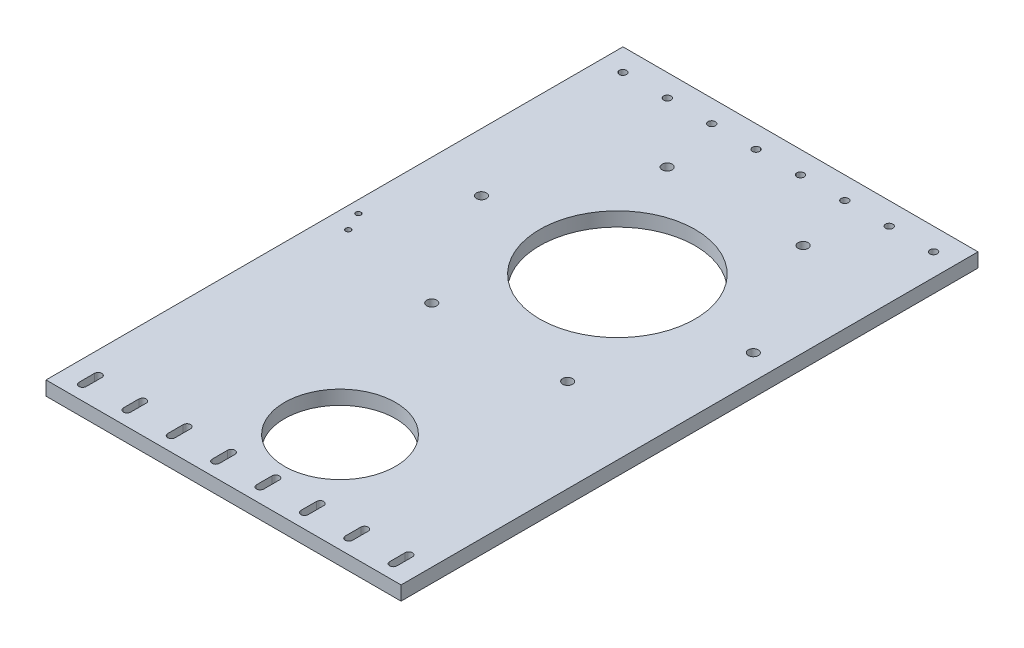
SolidWorks part; units mm, degrees
ref_plane "Front Plane" through (0, 0, 0) normal (0, 0, 1) x (1, 0, 0)
ref_plane "Top Plane" through (0, 0, 0) normal (0, 1, 0) x (1, 0, 0)
ref_plane "Right Plane" through (0, 0, 0) normal (1, 0, 0) x (0, 0, -1)
sketch "Sketch1" plane through (0, 0, 0) normal (0, 1, 0) x (1, 0, 0)
  line L0 (87.5, 260) -> (87.5, 0) construction
  line L1 (0, 0) -> (160, 0)
  line L2 (0, 0) -> (0, 260)
  line L3 (0, 260) -> (160, 260)
  line L4 (160, 0) -> (160, 260)
  line L5 (87.5, 170) -> (148.75, 170) construction
  line L6 (10, 6.5) -> (10, 13.5) construction
  line L7 (5.4755, 135.2989) -> (9.5163, 126.7011) construction
  line L8 (22, 0) -> (22, 260) construction
  line L9 (22, 136) -> (0, 136) construction
  line L10 (22, 126) -> (0, 126) construction
  line L11 (0, 136) -> (0, 126) construction
  line L12 (17.3003, 136) -> (22, 126) construction
  line L13 (8.35, 6.5) -> (8.35, 13.5)
  line L14 (11.65, 6.5) -> (11.65, 13.5)
  line L15 (10, 250) -> (10, 0) construction
  line L16 (31.65, 6.5) -> (31.65, 13.5)
  line L17 (28.35, 6.5) -> (28.35, 13.5)
  line L18 (30, 6.5) -> (30, 13.5) construction
  line L19 (51.65, 6.5) -> (51.65, 13.5)
  line L20 (48.35, 6.5) -> (48.35, 13.5)
  line L21 (50, 6.5) -> (50, 13.5) construction
  line L22 (71.65, 6.5) -> (71.65, 13.5)
  line L23 (68.35, 6.5) -> (68.35, 13.5)
  line L24 (70, 6.5) -> (70, 13.5) construction
  line L25 (91.65, 6.5) -> (91.65, 13.5)
  line L26 (88.35, 6.5) -> (88.35, 13.5)
  line L27 (90, 6.5) -> (90, 13.5) construction
  line L28 (111.65, 6.5) -> (111.65, 13.5)
  line L29 (108.35, 6.5) -> (108.35, 13.5)
  line L30 (110, 6.5) -> (110, 13.5) construction
  line L31 (131.65, 6.5) -> (131.65, 13.5)
  line L32 (128.35, 6.5) -> (128.35, 13.5)
  line L33 (130, 6.5) -> (130, 13.5) construction
  line L34 (151.65, 6.5) -> (151.65, 13.5)
  line L35 (148.35, 6.5) -> (148.35, 13.5)
  line L36 (150, 6.5) -> (150, 13.5) construction
  line L37 (10, 250) -> (30, 250) construction
  circle A0 centre (87.5, 170) radius 35
  circle A1 centre (87.5, 45) radius 25
  circle A2 centre (87.5, 170) radius 61.25 construction
  circle A3 centre (148.75, 170) radius 2.25
  circle A4 centre (118.125, 116.9559) radius 2.25
  circle A5 centre (56.875, 116.9559) radius 2.25
  circle A6 centre (26.25, 170) radius 2.25
  circle A7 centre (56.875, 223.0441) radius 2.25
  circle A8 centre (118.125, 223.0441) radius 2.25
  circle A10 centre (5.4755, 135.2989) radius 1.175
  circle A11 centre (9.5163, 126.7011) radius 1.175
  circle A12 centre (87.5, 170) radius 78 construction
  circle A13 centre (10, 250) radius 1.65
  arc A14 (8.35, 6.5) -> (11.65, 6.5) centre (10, 6.5) ccw
  arc A15 (11.65, 13.5) -> (8.35, 13.5) centre (10, 13.5) ccw
  circle A16 centre (30, 250) radius 1.65
  arc A17 (28.35, 6.5) -> (31.65, 6.5) centre (30, 6.5) ccw
  arc A18 (31.65, 13.5) -> (28.35, 13.5) centre (30, 13.5) ccw
  circle A19 centre (50, 250) radius 1.65
  arc A20 (48.35, 6.5) -> (51.65, 6.5) centre (50, 6.5) ccw
  arc A21 (51.65, 13.5) -> (48.35, 13.5) centre (50, 13.5) ccw
  circle A22 centre (70, 250) radius 1.65
  arc A23 (68.35, 6.5) -> (71.65, 6.5) centre (70, 6.5) ccw
  arc A24 (71.65, 13.5) -> (68.35, 13.5) centre (70, 13.5) ccw
  circle A25 centre (90, 250) radius 1.65
  arc A26 (88.35, 6.5) -> (91.65, 6.5) centre (90, 6.5) ccw
  arc A27 (91.65, 13.5) -> (88.35, 13.5) centre (90, 13.5) ccw
  circle A28 centre (110, 250) radius 1.65
  arc A29 (108.35, 6.5) -> (111.65, 6.5) centre (110, 6.5) ccw
  arc A30 (111.65, 13.5) -> (108.35, 13.5) centre (110, 13.5) ccw
  circle A31 centre (130, 250) radius 1.65
  arc A32 (128.35, 6.5) -> (131.65, 6.5) centre (130, 6.5) ccw
  arc A33 (131.65, 13.5) -> (128.35, 13.5) centre (130, 13.5) ccw
  circle A34 centre (150, 250) radius 1.65
  arc A35 (148.35, 6.5) -> (151.65, 6.5) centre (150, 6.5) ccw
  arc A36 (151.65, 13.5) -> (148.35, 13.5) centre (150, 13.5) ccw
  point P15 (87.5, 170)
  point P29 (10, 10)
  point P42 (7.4959, 131)
  point P43 (0, 131)
  point P55 (30, 10)
  point P65 (50, 10)
  point P74 (70, 10)
  point P83 (90, 10)
  point P92 (110, 10)
  point P101 (130, 10)
  point P110 (150, 10)
  dimension "D3" = 70
  dimension "D4" = 50
  dimension "D7" = 122.5
  dimension "D8" = 4.5
  dimension "D11" = 124
  dimension "D13" = 2.35
  dimension "D16" = 156
  dimension "D19" = 3.3
  dimension "D24" = 240
  dimension "D1" = 160
  dimension "D2" = 260
  dimension "D5" = 125
  dimension "D6" = 90
  dimension "D10" = 61.25
  dimension "D12" = 65.5
  dimension "D14" = 9.5
  dimension "D15" = 10
  dimension "D17" = 11
  dimension "D18" = 72.5
  dimension "D20" = 10
  dimension "D21" = 10
  dimension "D22" = 3.3
  dimension "D23" = 7
  dimension "D26" = 20
  dimension "D25" = 8
  dimension "D9" = 6
extrude "Boss-Extrude1" add sketch "Sketch1" along normal blind 6.35 contours A1 | A0 | A4 | A8 | A7 | A6 | L4 L3 L2 L1 | A3 | A5 | A11 | A10 | A28 | A25 | A31 | A34 | A22 | A19 | A16 | A13 | L14 A15 L13 A14 | L16 A18 L17 A17 | L19 A21 L20 A20 | L22 A24 L23 A23 | L25 A27 L26 A26 | L28 A30 L29 A29 | L31 A33 L32 A32 | L34 A36 L35 A35
